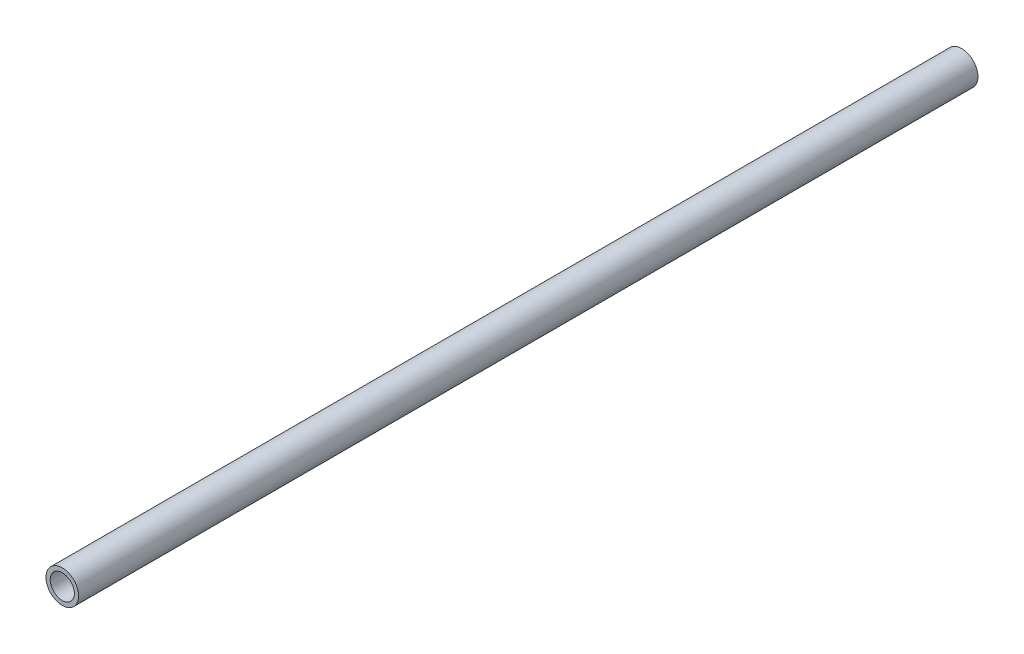
SolidWorks part; units mm, degrees
ref_plane "Front Plane" through (0, 0, 0) normal (0, 0, 1) x (1, 0, 0)
ref_plane "Top Plane" through (0, 0, 0) normal (0, 1, 0) x (1, 0, 0)
ref_plane "Right Plane" through (0, 0, 0) normal (1, 0, 0) x (0, 0, -1)
sketch "Sketch1" plane through (0, 0, 0) normal (0, 0, 1) x (1, 0, 0)
  circle A0 centre (0, 0) radius 4.699
  circle A1 centre (0, 0) radius 6.35
  dimension "D1" = 12.7
  dimension "D2" = 9.398
extrude "Boss-Extrude1" add sketch "Sketch1" against normal up to surface (350 mm away)
